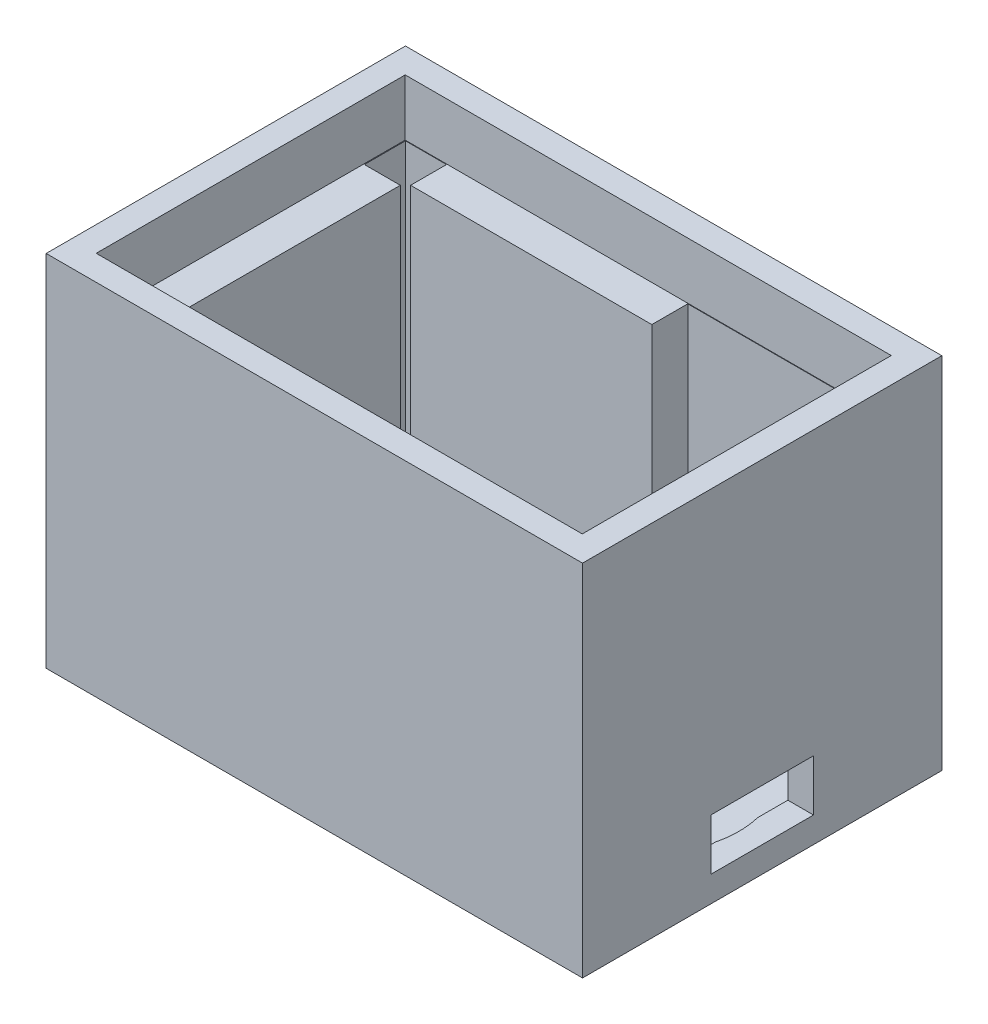
SolidWorks part; units mm, degrees
ref_plane "Front Plane" through (0, 0, 0) normal (0, 0, 1) x (1, 0, 0)
ref_plane "Top Plane" through (0, 0, 0) normal (0, 1, 0) x (1, 0, 0)
ref_plane "Right Plane" through (0, 0, 0) normal (1, 0, 0) x (0, 0, -1)
sketch "Sketch1" plane through (0, 0, 0) normal (0, 1, 0) x (1, 0, 0)
  line L1 (0, 0) -> (104.5, 0)
  line L2 (0, 0) -> (0, 70)
  line L3 (0, 70) -> (104.5, 70)
  line L4 (104.5, 0) -> (104.5, 70)
  dimension "D1" = 104.5
  dimension "D2" = 70
extrude "Boss-Extrude1" add sketch "Sketch1" along normal blind 70
sketch "Sketch2" plane through (0, 70, 0) normal (0, 1, 0) x (1, 0, 0)
  line L1 (4.85, 65.1) -> (99.55, 65.1)
  line L2 (4.85, 65.1) -> (4.85, 4.9)
  line L3 (4.85, 4.9) -> (99.55, 4.9)
  line L4 (99.55, 65.1) -> (99.55, 4.9)
  line L5 (0, 70) -> (0, 0) construction
  line L6 (104.5, 70) -> (0, 70) construction
  dimension "D1" = 94.7
  dimension "D2" = 60.2
  dimension "D3" = 4.85
  dimension "D4" = 4.9
extrude "Cut-Extrude1" cut sketch "Sketch2" against normal blind 11
sketch "Sketch3" plane through (0, 59, 0) normal (0, 1, 0) x (1, 0, 0)
  line L23 (0, 0) -> (104.5, 0) construction
  line L25 (4.85, 35) -> (117.3919, 35) construction
  line L27 (4.85, 65.1) -> (4.85, 4.9) construction
  line L28 (99.5, 39.1533) -> (99.5, 58)
  line L29 (90.5, 58) -> (99.5, 58)
  line L30 (90.5, 58) -> (90.5, 65)
  line L31 (60, 65) -> (90.5, 65)
  line L32 (60, 58) -> (60, 65)
  line L33 (13, 65) -> (13, 58)
  line L34 (5, 57) -> (12, 57)
  line L35 (5, 65) -> (5, 57)
  line L36 (5, 65) -> (13, 65)
  line L37 (88.1941, 12) -> (99.5, 12)
  line L38 (71.9073, 12) -> (76.8059, 12)
  line L39 (36.0475, 12) -> (65.0927, 12)
  line L40 (99.5, 12) -> (99.5, 30.8467)
  line L41 (13, 58) -> (60, 58)
  line L42 (12, 12) -> (12, 57)
  line L43 (12, 12) -> (30.9525, 12)
  arc A3 (99.5, 30.8467) -> (99.5, 39.1533) centre (82.5, 35) ccw
  arc A4 (88.1941, 12) -> (76.8059, 12) centre (82.5, 11.2) cw
  arc A5 (71.9073, 12) -> (65.0927, 12) centre (68.5, 11.2) cw
  arc A6 (36.0475, 12) -> (30.9525, 12) centre (33.5, 9.6) cw
  dimension "D19" = 35
  dimension "D20" = 35
extrude "Cut-Extrude3" cut sketch "Sketch3" against normal blind 55
sketch "Sketch5" plane through (104.5, 0, 0) normal (1, 0, 0) x (0, 0, -1)
  line L0 (0, 0) -> (70, 0) construction
  line L1 (25, 15) -> (45, 15)
  line L2 (25, 15) -> (25, 5)
  line L3 (25, 5) -> (45, 5)
  line L4 (45, 15) -> (45, 5)
  line L5 (0, 70) -> (0, 0) construction
  dimension "D1" = 20
  dimension "D2" = 10
  dimension "D3" = 5
  dimension "D4" = 25
extrude "Cut-Extrude4" cut sketch "Sketch5" against normal blind 10
